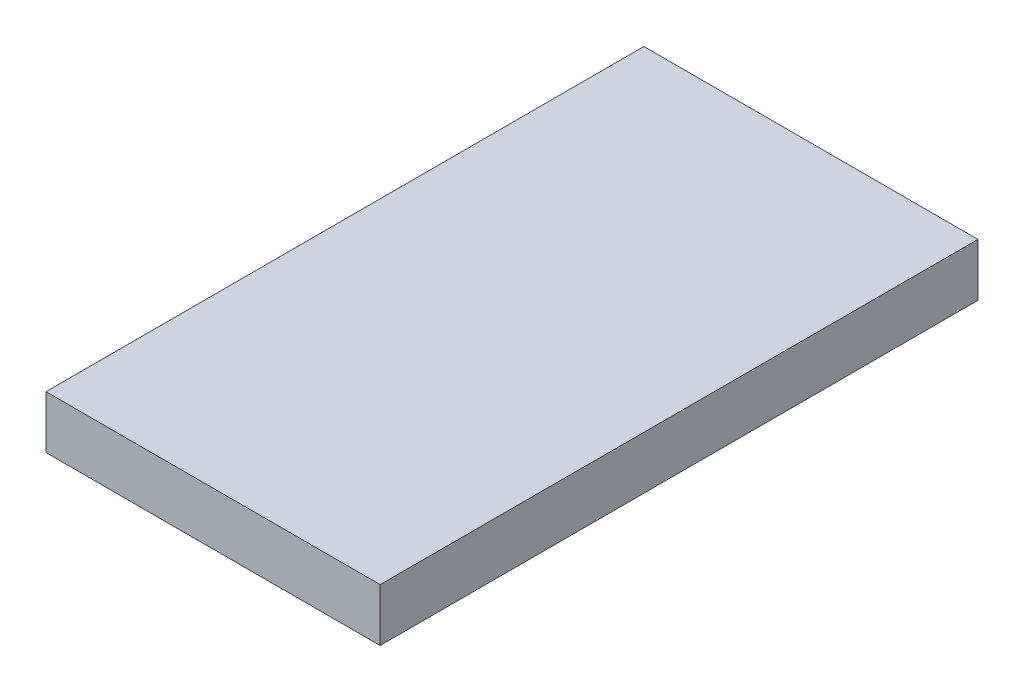
SolidWorks part; units mm, degrees
material "Copper"
ref_plane "Front Plane" through (0, 0, 0) normal (0, 0, 1) x (1, 0, 0)
ref_plane "Top Plane" through (0, 0, 0) normal (0, 1, 0) x (1, 0, 0)
ref_plane "Right Plane" through (0, 0, 0) normal (1, 0, 0) x (0, 0, -1)
sketch "Sketch1" plane through (0, 0, 0) normal (0, 1, 0) x (1, 0, 0)
  line L1 (0, 0) -> (120.65, 0)
  line L2 (0, 0) -> (0, 215.9)
  line L3 (0, 215.9) -> (120.65, 215.9)
  line L4 (120.65, 0) -> (120.65, 215.9)
  dimension "D1" = 120.65
  dimension "D2" = 215.9
extrude "Base Extrude" add sketch "Sketch1" along normal blind 19.05
